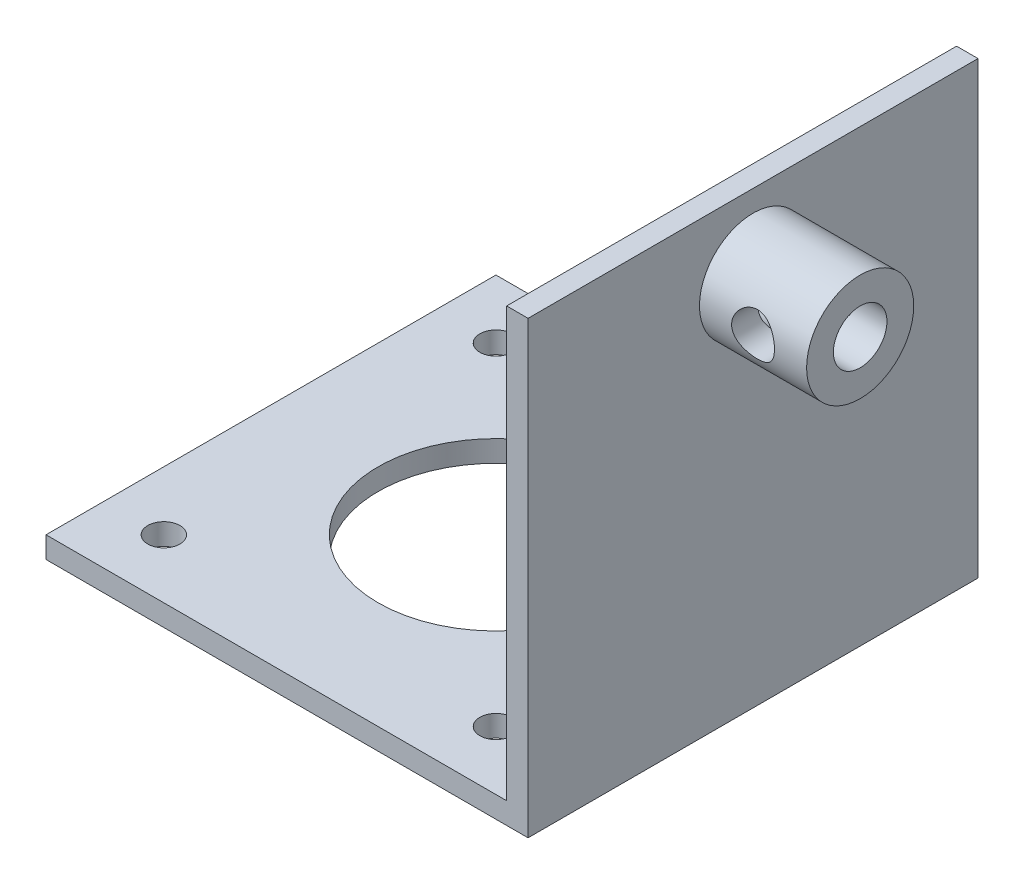
SolidWorks part; units mm, degrees
material "5052-H36"
ref_plane "前视基准面" through (0, 0, 0) normal (0, 0, 1) x (1, 0, 0)
ref_plane "上视基准面" through (0, 0, 0) normal (0, 1, 0) x (1, 0, 0)
ref_plane "右视基准面" through (0, 0, 0) normal (1, 0, 0) x (0, 0, -1)
sketch "草图1" plane through (0, 0, 0) normal (0, 1, 0) x (1, 0, 0)
  line L1 (0, 0) -> (45, 0)
  line L2 (0, 0) -> (0, 42)
  line L3 (0, 42) -> (45, 42)
  line L4 (45, 0) -> (45, 42)
extrude "凸台-拉伸1" add sketch "草图1" along normal blind 2
sketch "草图2" plane through (0, 2, 0) normal (0, 1, 0) x (1, 0, 0)
  line L0 (0, 0) -> (0, 21)
  line L1 (0, 42) -> (0, 0) construction
  circle A0 centre (21, 21) radius 11
  circle A1 centre (5.5, 5.5) radius 1.5
  circle A2 centre (5.5, 36.5) radius 1.5
  circle A3 centre (36.5, 36.5) radius 1.5
  circle A4 centre (36.5, 5.5) radius 1.5
extrude "切除-拉伸1" cut sketch "草图2" against normal blind 2 contours A2 | A0 | A1 | A4 | A3
sketch "草图3" plane through (0, 2, 0) normal (0, 1, 0) x (1, 0, 0)
  line L0 (45, 42) -> (43, 42)
  line L1 (45, 42) -> (0, 42) construction
  line L2 (43, 42) -> (43, 0)
  line L3 (0, 0) -> (45, 0) construction
  line L4 (43, 0) -> (45, 0)
  line L5 (45, 0) -> (45, 42)
extrude "凸台-拉伸2" add sketch "草图3" along normal blind 40
sketch "草图4" plane through (45, 0, 0) normal (1, 0, 0) x (0, 0, -1)
  line L0 (21, 0) -> (21, 35)
  line L1 (0, 0) -> (42, 0) construction
  circle A0 centre (21, 35) radius 5
  circle A1 centre (21, 35) radius 2.5
extrude "凸台-拉伸3" add sketch "草图4" along normal blind 10
sketch "草图5" plane through (0, 0, 0) normal (0, 0, 1) x (1, 0, 0)
  line L0 (45, 35) -> (50, 35)
  line L1 (45, 30) -> (45, 40) construction
  circle A0 centre (50, 35) radius 2
extrude "切除-拉伸2" cut sketch "草图5" against normal through all
